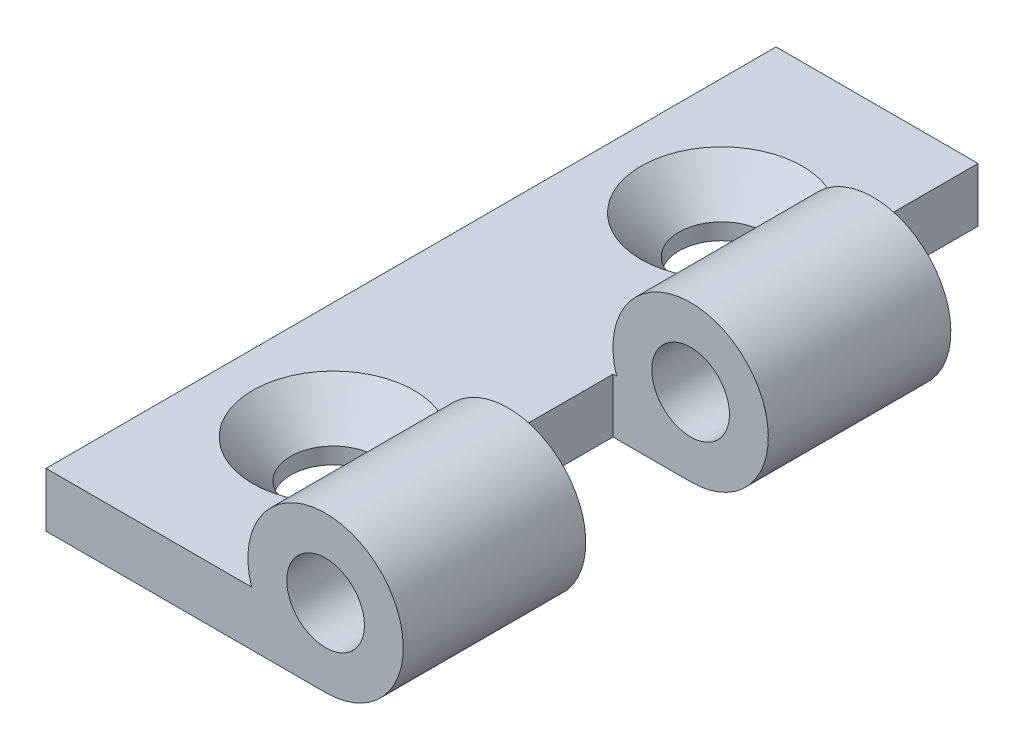
SolidWorks part; units mm, degrees
ref_plane "Front Plane" through (0, 0, 0) normal (0, 0, 1) x (1, 0, 0)
ref_plane "Top Plane" through (0, 0, 0) normal (0, 1, 0) x (1, 0, 0)
ref_plane "Right Plane" through (0, 0, 0) normal (1, 0, 0) x (0, 0, -1)
sketch "Sketch1" plane through (0, 0, 0) normal (0, 0, 1) x (1, 0, 0)
  line L0 (0, -5) -> (-18, -5)
  line L1 (-18, -5) -> (-18, -1.5)
  line L2 (-18, -1.5) -> (-4.7697, -1.5)
  circle A0 centre (0, 0) radius 5
  circle A1 centre (0, 0) radius 2.5
  dimension "D1" = 10
  dimension "D2" = 5
  dimension "D3" = 3.5
  dimension "D4" = 18
extrude "Boss-Extrude1" add sketch "Sketch1" along normal mid plane 47 contours A0 L2 L1 L0 | A0 A1
sketch "Sketch2" plane through (0, -1.5, 0) normal (0, 1, 0) x (1, 0, 0)
  line L0 (-10.5, 12.5) -> (-10.5, -12.5) construction
  point P0 (-10.5, 12.5)
  point P1 (-10.5, -12.5)
  point P2 (-10.5, 0)
  dimension "D1" = 25
  dimension "D2" = 10.5
hole_wizard "CSK for M5 Countersunk Flat Head Screw1" positions "Sketch2" profile "Sketch3" countersink size "M5" standard "ISO" end condition through all
sketch "Sketch3" plane through (-10.5, -1.5, -12.5) normal (1, 0, 0) x (0, 0, 1)
  line L0 (0, 0) -> (0, 3.5)
  line L1 (0, 3.5) -> (2.75, 3.5)
  line L2 (2.75, 3.5) -> (2.75, 2.45)
  line L3 (2.75, 2.45) -> (5.2, 0)
  line L5 (5.2, 0) -> (0, 0)
  line L6 (-2.75, 2.45) -> (-5.2, 0) construction
  line L11 (0, -6.35) -> (0, 107.95) construction
  dimension "Thru Hole Dia." = 5.5
  dimension "Thru Hole Depth" = 3.5
  dimension "Near C'Sink Dia." = 10.4
  dimension "Near C'Sink Angle" = 90
sketch "Sketch4" plane through (0, 0, 0) normal (0, 1, 0) x (1, 0, 0)
  line L0 (5, 23.5) -> (-5, 23.5) construction
  line L1 (5, 23.5) -> (-5, 23.5)
  line L2 (5, 23.5) -> (5, 11.75)
  line L3 (5, 11.75) -> (-5, 11.75)
  line L4 (-5, 23.5) -> (-5, 11.75)
  line L5 (-5, 23.5) -> (-5, -23.5) construction
  line L6 (5, -23.5) -> (5, 23.5) construction
  line L8 (5, 0) -> (-5, 0)
  line L9 (5, 0) -> (5, -11.75)
  line L10 (5, -11.75) -> (-5, -11.75)
  line L11 (-5, 0) -> (-5, -11.75)
  dimension "D1" = 11.75
  dimension "D2" = 11.75
  dimension "D3" = 11.75
extrude "Cut-Extrude1" cut sketch "Sketch4" against normal through all both and the other way through all
